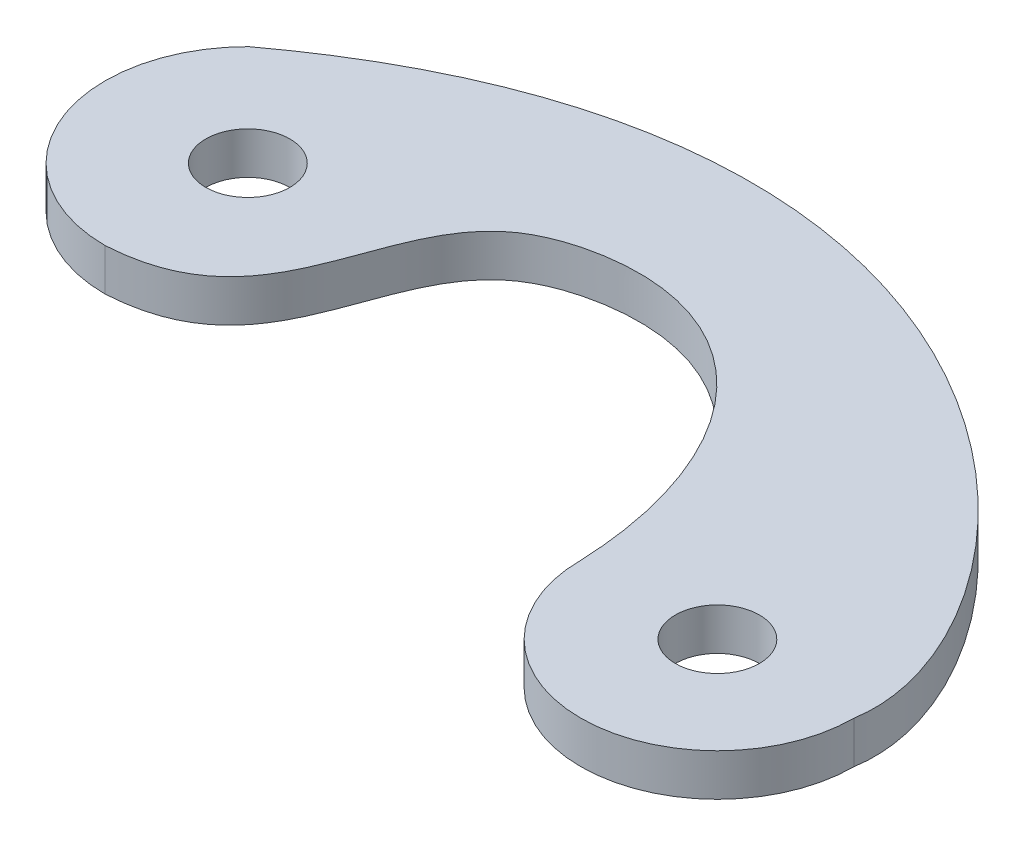
SolidWorks part; units mm, degrees
ref_plane "Front Plane" through (0, 0, 0) normal (0, 0, 1) x (1, 0, 0)
ref_plane "Top Plane" through (0, 0, 0) normal (0, 1, 0) x (1, 0, 0)
ref_plane "Right Plane" through (0, 0, 0) normal (1, 0, 0) x (0, 0, -1)
sketch "Sketch1" plane through (0, 0, 0) normal (0, 1, 0) x (1, 0, 0)
  circle A0 centre (35.9831, -12.3701) radius 2
  circle A1 centre (66.7592, -20.8132) radius 2
  arc A2 (60.2592, -20.8132) -> (73.2592, -20.8132) centre (66.7592, -20.8132) ccw
  arc A3 (31.2019, -7.552) -> (35.9831, -19.1579) centre (35.9831, -12.3701) ccw
  spline S0 degree 3 poles (73.2592, -20.8132) (74.7259, -12.216) (54.126, 9.5259) (31.2019, -7.552) knots 0 0 0 0 1 1 1 1
  spline S1 degree 3 poles (35.9831, -19.1579) (43.2508, -18.7355) (40.8488, -9.6749) (54.4002, -5.8365) (59.9382, -12.8504) (60.2592, -20.8132) knots 0 0 0 0 0.397903 0.497903 1 1 1 1
extrude "Boss-Extrude1" add sketch "Sketch1" along normal blind 2
